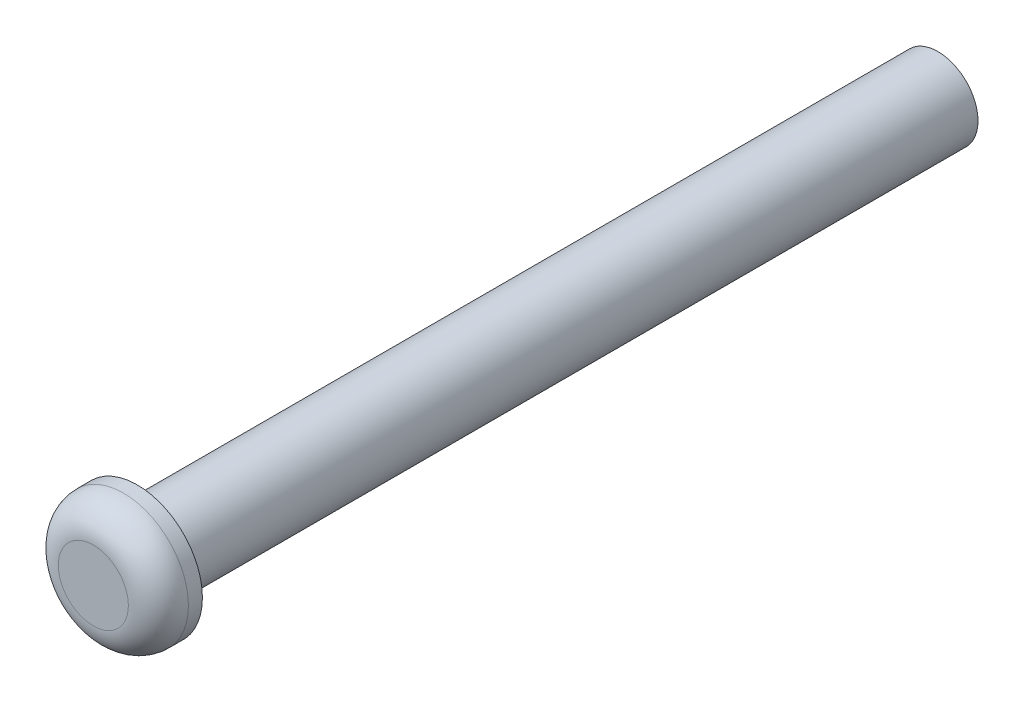
SolidWorks part; units mm, degrees
ref_plane "前视基准面" through (0, 0, 0) normal (0, 0, 1) x (1, 0, 0)
ref_plane "上视基准面" through (0, 0, 0) normal (0, 1, 0) x (1, 0, 0)
ref_plane "右视基准面" through (0, 0, 0) normal (1, 0, 0) x (0, 0, -1)
sketch "草图1" plane through (0, 0, 0) normal (0, 0, 1) x (1, 0, 0)
  circle A0 centre (0, 0) radius 2
  dimension "D1" = 4
extrude "凸台-拉伸1" add sketch "草图1" along normal blind 40 contours A0
sketch "草图2" plane through (0, 0, 40) normal (0, 0, 1) x (1, 0, 0)
  circle A0 centre (0, 0) radius 3.25
extrude "凸台-拉伸2" add sketch "草图2" along normal blind 2.2
fillet "圆角1" radius 1.5 1 edges at (3.25, 0, 42.2)
